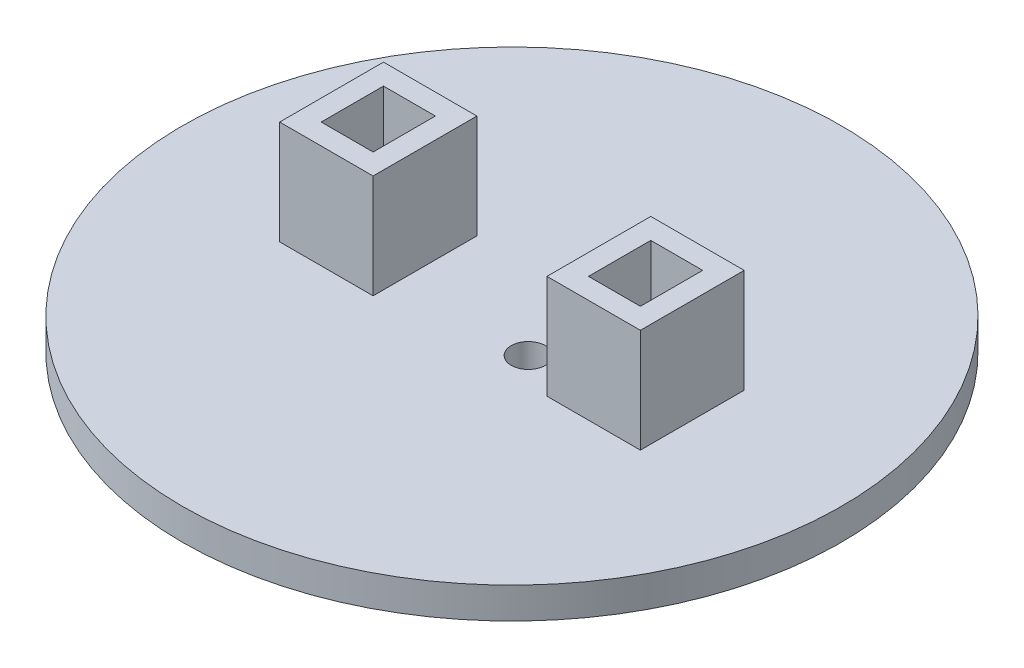
SolidWorks part; units mm, degrees
ref_plane "Front Plane" through (0, 0, 0) normal (0, 0, 1) x (1, 0, 0)
ref_plane "Top Plane" through (0, 0, 0) normal (0, 1, 0) x (1, 0, 0)
ref_plane "Right Plane" through (0, 0, 0) normal (1, 0, 0) x (0, 0, -1)
sketch "Sketch1" plane through (0, 0, 0) normal (0, 1, 0) x (1, 0, 0)
  line L0 (4.08, -2.5) -> (4.08, 2.5) construction
  line L2 (0, 0) -> (4.08, 0) construction
  circle A0 centre (0, 0) radius 31.75
  circle A1 centre (4.08, 2.5) radius 1.65
  circle A3 centre (4.08, -2.5) radius 1.65
  point P6 (0, 0)
  point P7 (0, 0)
  dimension "D1" = 63.5
  dimension "D4" = 3.3
  dimension "D6" = 3.3
  dimension "D2" = 5
  dimension "D3" = 4.08
extrude "Boss-Extrude1" add sketch "Sketch1" along normal blind 3
sketch "Sketch2" plane through (0, 3, 0) normal (0, 1, 0) x (1, 0, 0)
  line L0 (-10.375, 0) -> (10.375, 0) construction
  line L1 (8.375, 5) -> (17.375, 5)
  line L2 (-15.375, 3) -> (-10.375, 3)
  line L3 (-15.375, 3) -> (-15.375, -3)
  line L4 (-15.375, -3) -> (-10.375, -3)
  line L5 (-10.375, 3) -> (-10.375, -3)
  line L6 (10.375, 3) -> (15.375, 3)
  line L7 (10.375, 3) -> (10.375, -3)
  line L8 (10.375, -3) -> (15.375, -3)
  line L9 (15.375, 3) -> (15.375, -3)
  line L10 (-17.375, 5) -> (-8.375, 5)
  line L11 (-17.375, 5) -> (-17.375, -5)
  line L12 (-17.375, -5) -> (-8.375, -5)
  line L13 (-8.375, 5) -> (-8.375, -5)
  line L14 (8.375, 5) -> (8.375, -5)
  line L15 (8.375, -5) -> (17.375, -5)
  line L16 (17.375, 5) -> (17.375, -5)
  point P3 (0, 0)
  point P20 (10.375, 0)
  point P21 (-10.375, 0)
  dimension "D1" = 20.75
  dimension "D2" = 5
  dimension "D3" = 6
  dimension "D4" = 5
  dimension "D5" = 6
  dimension "D6" = 9
  dimension "D7" = 10
  dimension "D8" = 2
  dimension "D9" = 2
  dimension "D10" = 2
  dimension "D11" = 2
  dimension "D12" = 9
  dimension "D13" = 10
extrude "Boss-Extrude2" add sketch "Sketch2" along normal blind 10
equation "\"D6@Sketch1\"=\"D4@Sketch1\""
